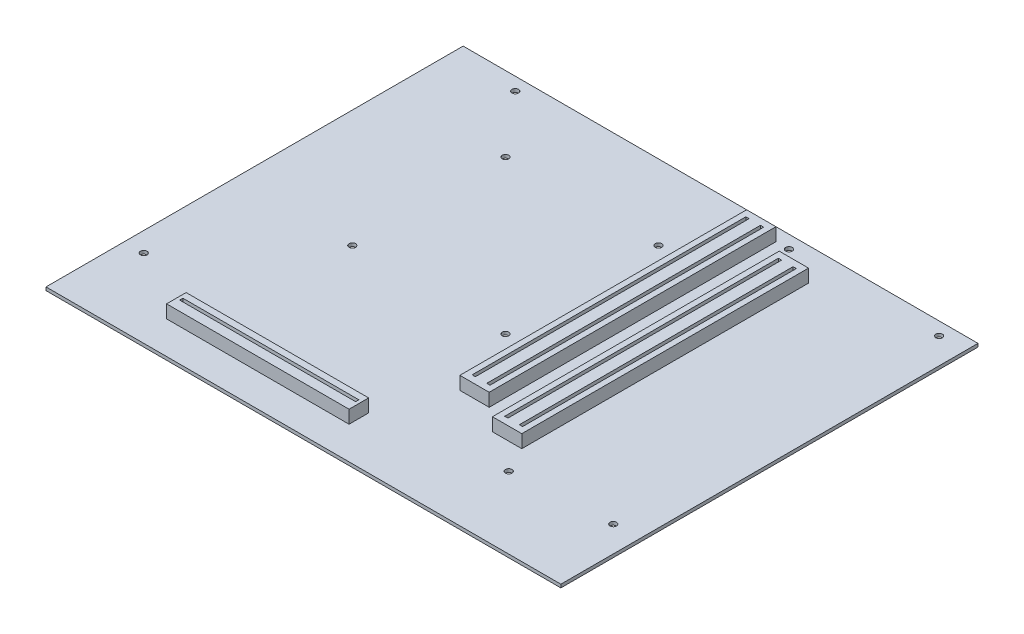
SolidWorks part; units mm, degrees
ref_plane "Front Plane" through (0, 0, 0) normal (0, 0, 1) x (1, 0, 0)
ref_plane "Top Plane" through (0, 0, 0) normal (0, 1, 0) x (1, 0, 0)
ref_plane "Right Plane" through (0, 0, 0) normal (1, 0, 0) x (0, 0, -1)
sketch "Sketch1" plane through (0, 0, 0) normal (0, 1, 0) x (1, 0, 0)
  line L0 (0, 0) -> (250.825, 0)
  line L1 (250.825, 0) -> (250.825, 203.2)
  line L2 (250.825, 203.2) -> (0, 203.2)
  line L3 (0, 203.2) -> (0, 0)
  circle A0 centre (31.75, 196.85) radius 1.5875
  circle A1 centre (165.1, 196.85) radius 1.5875
  circle A2 centre (238.252, 196.85) radius 1.5875
  circle A3 centre (238.252, 38.1) radius 1.5875
  circle A4 centre (190.5, 34.925) radius 1.5875
  circle A5 centre (9.525, 38.1) radius 1.5875
  circle A6 centre (57.15, 166.6875) radius 1.5875
  circle A7 centre (131.7625, 166.6875) radius 1.5875
  circle A8 centre (131.7625, 92.075) radius 1.5875
  circle A9 centre (57.15, 92.075) radius 1.5875
  point P25 (0, 0)
  point P26 (0, 0)
  point P27 (0, 0)
  point P28 (0, 0)
  point P29 (0, 0)
  point P30 (0, 0)
  point P31 (60.0837, 176.1157)
  point P32 (0, 0)
  dimension "D6" = 3.175
  dimension "D1" = 250.825
  dimension "D2" = 203.2
  dimension "D3" = 31.75
  dimension "D4" = 165.1
  dimension "D5" = 238.252
  dimension "D7" = 6.35
  dimension "D8" = 38.1
  dimension "D9" = 60.325
  dimension "D10" = 34.925
  dimension "D11" = 9.525
  dimension "D12" = 74.6125
  dimension "D13" = 74.6125
  dimension "D14" = 36.5125
  dimension "D15" = 57.15
extrude "Boss-Extrude1" add sketch "Sketch1" along normal blind 1.5875
sketch "Sketch2" plane through (0, 1.5875, 0) normal (0, 1, 0) x (1, 0, 0)
  line L0 (144.4625, 196.85) -> (144.4625, 57.15)
  line L1 (144.4625, 57.15) -> (158.75, 57.15)
  line L2 (158.75, 57.15) -> (158.75, 196.85)
  line L3 (158.75, 196.85) -> (144.4625, 196.85)
  line L4 (250.825, 203.2) -> (0, 203.2) construction
  line L5 (172.6406, 184.15) -> (174.2281, 184.15)
  line L6 (169.8625, 187.325) -> (184.15, 187.325)
  line L7 (169.8625, 187.325) -> (169.8625, 47.625)
  line L8 (169.8625, 47.625) -> (184.15, 47.625)
  line L9 (184.15, 187.325) -> (184.15, 47.625)
  line L10 (147.2406, 193.675) -> (148.8281, 193.675)
  line L11 (147.2406, 193.675) -> (147.2406, 60.325)
  line L12 (147.2406, 60.325) -> (148.8281, 60.325)
  line L13 (148.8281, 193.675) -> (148.8281, 60.325)
  line L14 (154.3844, 193.675) -> (155.9719, 193.675)
  line L15 (154.3844, 193.675) -> (154.3844, 60.325)
  line L16 (154.3844, 60.325) -> (155.9719, 60.325)
  line L17 (155.9719, 193.675) -> (155.9719, 60.325)
  line L18 (172.6406, 184.15) -> (172.6406, 50.8)
  line L19 (172.6406, 50.8) -> (174.2281, 50.8)
  line L20 (174.2281, 184.15) -> (174.2281, 50.8)
  line L21 (179.7844, 184.15) -> (181.3719, 184.15)
  line L22 (179.7844, 184.15) -> (179.7844, 50.8)
  line L23 (179.7844, 50.8) -> (181.3719, 50.8)
  line L24 (181.3719, 184.15) -> (181.3719, 50.8)
  line L25 (0, 203.2) -> (0, 0) construction
  line L26 (42.8625, 25.4) -> (131.7625, 25.4)
  line L27 (42.8625, 25.4) -> (42.8625, 15.875)
  line L28 (42.8625, 15.875) -> (131.7625, 15.875)
  line L29 (131.7625, 25.4) -> (131.7625, 15.875)
  line L30 (0, 0) -> (250.825, 0) construction
  line L32 (44.45, 22.225) -> (130.175, 22.225)
  line L33 (44.45, 22.225) -> (44.45, 20.6375)
  line L34 (44.45, 20.6375) -> (130.175, 20.6375)
  line L35 (130.175, 22.225) -> (130.175, 20.6375)
  point P27 (147.2406, 127)
  point P28 (144.4625, 127)
  point P29 (172.6406, 117.475)
  point P30 (169.8625, 117.475)
  point P31 (148.0344, 193.675)
  point P32 (155.1781, 193.675)
  point P33 (173.4344, 184.15)
  point P34 (180.5781, 184.15)
  dimension "D1" = 144.4625
  dimension "D3" = 6.35
  dimension "D4" = 139.7
  dimension "D5" = 139.7
  dimension "D6" = 14.2875
  dimension "D7" = 15.875
  dimension "D8" = 169.8625
  dimension "D2" = 14.2875
  dimension "D9" = 1.5875
  dimension "D10" = 133.35
  dimension "D11" = 3.5719
  dimension "D12" = 3.5719
  dimension "D13" = 3.5719
  dimension "D14" = 3.5719
  dimension "D15" = 42.8625
  dimension "D16" = 88.9
  dimension "D17" = 9.525
  dimension "D18" = 25.4
  dimension "D19" = 3.175
  dimension "D20" = 1.5875
  dimension "D21" = 1.5875
  dimension "D22" = 1.5875
extrude "Boss-Extrude2" add sketch "Sketch2" along normal blind 6.35
equation "\"D11@Sketch2\"=\"D2@Sketch2\"/4"
equation "\"D12@Sketch2\"=\"D11@Sketch2\""
equation "\"D13@Sketch2\"=\"D11@Sketch2\""
equation "\"D14@Sketch2\"=\"D11@Sketch2\""
